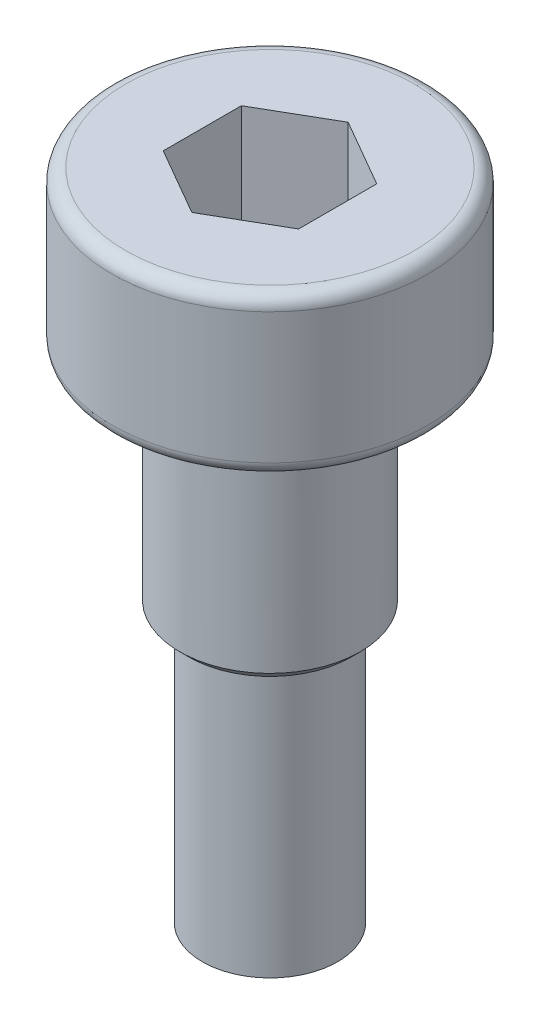
SolidWorks part; units mm, degrees
ref_plane "前视基准面" through (0, 0, 0) normal (0, 0, 1) x (1, 0, 0)
ref_plane "上视基准面" through (0, 0, 0) normal (0, 1, 0) x (1, 0, 0)
ref_plane "右视基准面" through (0, 0, 0) normal (1, 0, 0) x (0, 0, -1)
sketch "草图1" plane through (0, 0, 0) normal (0, 0, 1) x (1, 0, 0)
  line L0 (0, 3.5) -> (0, -15.6048) construction
  line L1 (0, 3.5) -> (-3.5, 3.5)
  line L2 (-3.5, 3.5) -> (-3.5, 0)
  line L3 (-3.5, 0) -> (-2, 0)
  line L4 (-2, 0) -> (-2, -5)
  line L5 (-2, -5) -> (-1.5, -5)
  line L6 (-1.5, -5) -> (-1.5, -11)
  line L7 (-1.5, -11) -> (0, -11)
  line L8 (0, 3.5) -> (0, -11)
  dimension "D1" = 4
  dimension "D2" = 6
  dimension "D3" = 3.5
  dimension "D4" = 7
  dimension "D5" = 5
  dimension "D6" = 3
revolve "旋转1" add sketch "草图1" angle 360 about L0
cosmetic thread "装饰螺纹线1" parameters "D2"=2.459
fillet "圆角1" radius 0.3 2 edges at (-3.5, 0, 0) (-3.5, 3.5, 0)
sketch "草图2" plane through (0, 3.5, 0) normal (0, 1, 0) x (1, 0, 0)
  line L1 (0, 1.7321) -> (-1.5, 0.866)
  line L2 (-1.5, 0.866) -> (-1.5, -0.866)
  line L3 (-1.5, -0.866) -> (0, -1.7321)
  line L4 (0, -1.7321) -> (1.5, -0.866)
  line L5 (1.5, -0.866) -> (1.5, 0.866)
  line L6 (1.5, 0.866) -> (0, 1.7321)
  circle A0 centre (0, 0) radius 1.5 construction
  dimension "D1" = 3
extrude "切除-拉伸1" cut sketch "草图2" against normal blind 2.4
chamfer "倒角1" distance 0.2 angle 45 1 edges at (-2, -5, 0)
